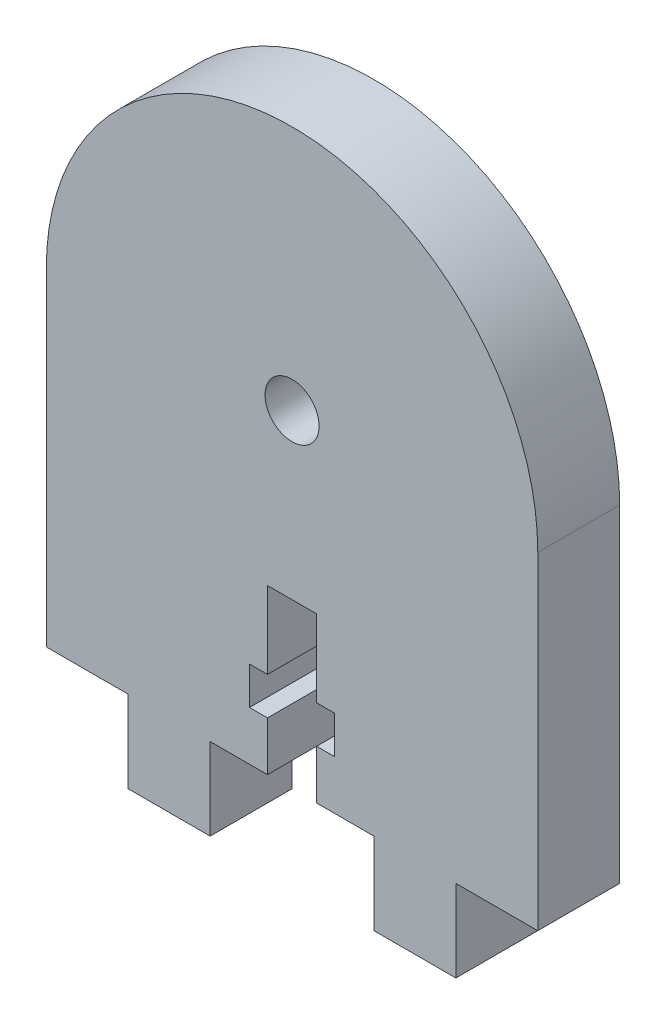
SolidWorks part; units mm, degrees
ref_plane "Front Plane" through (0, 0, 0) normal (0, 0, 1) x (1, 0, 0)
ref_plane "Top Plane" through (0, 0, 0) normal (0, 1, 0) x (1, 0, 0)
ref_plane "Right Plane" through (0, 0, 0) normal (1, 0, 0) x (0, 0, -1)
sketch "Sketch1" plane through (0, 0, 0) normal (0, 0, 1) x (1, 0, 0)
  line L0 (-10, 0) -> (-15, 0)
  line L1 (-15, 0) -> (-15, 20)
  line L2 (-15, 20) -> (15, 20) construction
  line L3 (15, 20) -> (15, 0)
  line L4 (15, 0) -> (10, 0)
  line L5 (0, 0) -> (0, 11.2208) construction
  line L6 (-1.5, 0) -> (-5, 0)
  line L7 (-5, -5) -> (-10, -5)
  line L8 (-10, -5) -> (-10, 0)
  line L9 (-5, -5) -> (-5, 0)
  line L10 (1.5, 0) -> (5, 0)
  line L11 (5, 0) -> (5, -5)
  line L12 (5, -5) -> (10, -5)
  line L13 (10, -5) -> (10, 0)
  line L14 (-1.5, 0) -> (1.5, 0) construction
  line L15 (1.5, 0) -> (1.5, 3)
  line L16 (1.5, 5.3) -> (2.6, 5.3)
  line L17 (-2.6, 3) -> (-2.6, 5.3)
  line L18 (2.6, 3) -> (1.5, 3)
  line L19 (1.5, 5.3) -> (1.5, 10)
  line L20 (1.5, 10) -> (-1.5, 10)
  line L21 (-1.5, 10) -> (-1.5, 5.3)
  line L22 (-1.5, 3) -> (-2.6, 3)
  line L23 (2.6, 5.3) -> (2.6, 3)
  line L24 (-2.6, 5.3) -> (-1.5, 5.3)
  line L25 (-1.5, 3) -> (-1.5, 0)
  line L26 (0, 10) -> (0, 0) construction
  arc A0 (-15, 20) -> (15, 20) centre (0, 20) cw
  circle A1 centre (0, 20) radius 1.65
  dimension "D3" = 3.3
  dimension "D1" = 5
  dimension "D2" = 20
  dimension "D4" = 10
  dimension "D5" = 5
  dimension "D6" = 5
  dimension "D7" = 5.2
  dimension "D8" = 3
  dimension "D9" = 2.3
  dimension "D10" = 3
  dimension "D11" = 10
extrude "Boss-Extrude1" add sketch "Sketch1" along normal blind 5
